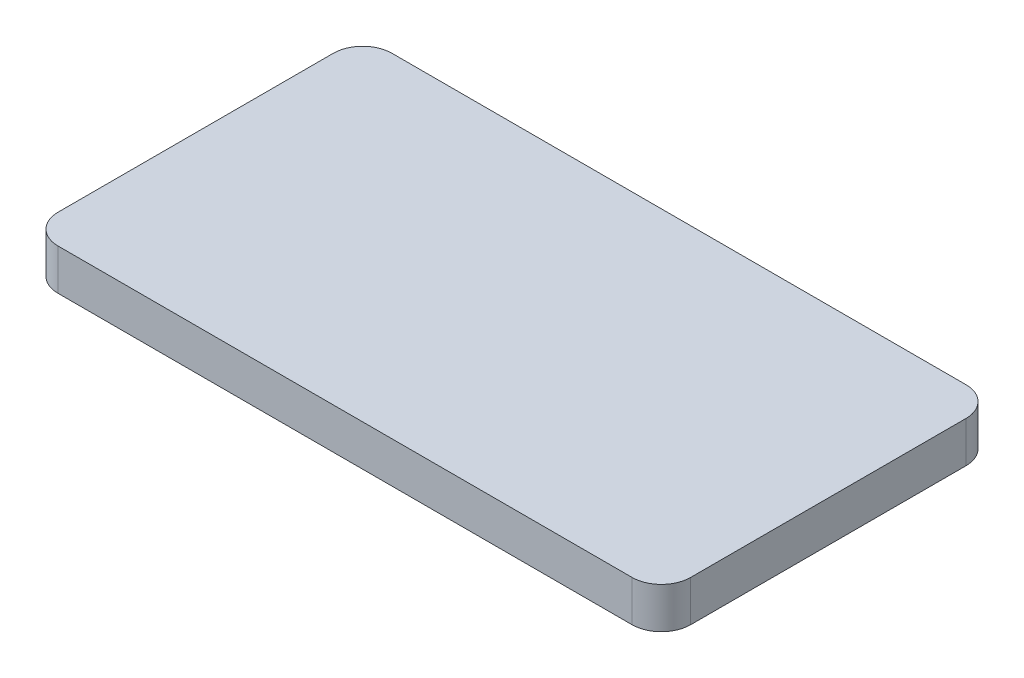
SolidWorks part; units mm, degrees
ref_plane "Front Plane" through (0, 0, 0) normal (0, 0, 1) x (1, 0, 0)
ref_plane "Top Plane" through (0, 0, 0) normal (0, 1, 0) x (1, 0, 0)
ref_plane "Right Plane" through (0, 0, 0) normal (1, 0, 0) x (0, 0, -1)
sketch "Sketch1" plane through (0, 0, 0) normal (0, 1, 0) x (1, 0, 0)
  line L1 (-49, 28.5) -> (49, 28.5)
  line L2 (-54, 23.5) -> (-54, -23.5)
  line L3 (-49, -28.5) -> (49, -28.5)
  line L4 (54, 23.5) -> (54, -23.5)
  line L5 (-54, 28.5) -> (54, -28.5) construction
  line L6 (-54, -28.5) -> (54, 28.5) construction
  arc A0 (49, 28.5) -> (54, 23.5) centre (49, 23.5) cw
  arc A1 (-49, 28.5) -> (-54, 23.5) centre (-49, 23.5) ccw
  arc A2 (49, -28.5) -> (54, -23.5) centre (49, -23.5) ccw
  arc A3 (-54, -23.5) -> (-49, -28.5) centre (-49, -23.5) ccw
  point P1 (0, 0)
  dimension "D3" = 5
  dimension "D4" = 5
  dimension "D1" = 108
  dimension "D2" = 57
extrude "Boss-Extrude1" add sketch "Sketch1" along normal blind 7
